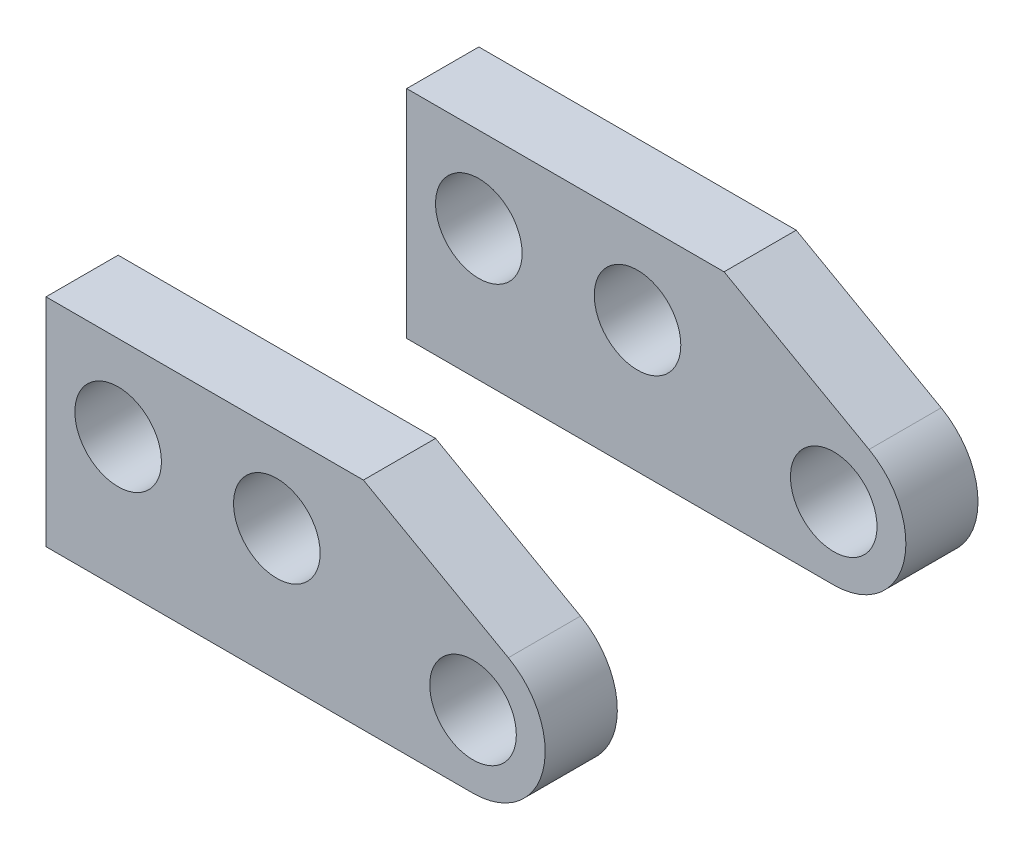
SolidWorks part; units mm, degrees
material "Thornel Mat VMA"
ref_plane "前视基准面" through (0, 0, 0) normal (0, 0, 1) x (1, 0, 0)
ref_plane "上视基准面" through (0, 0, 0) normal (0, 1, 0) x (1, 0, 0)
ref_plane "右视基准面" through (0, 0, 0) normal (1, 0, 0) x (0, 0, -1)
other "Configuration Table"
sketch "草图2" plane through (0, 0, 0) normal (0, 0, 1) x (1, 0, 0)
  line L0 (5.5, 3.75) -> (10.5237, 0.93)
  line L1 (-5.5, 3.75) -> (5.5, 3.75)
  line L2 (-5.5, 3.75) -> (-5.5, -3.75)
  line L3 (-5.5, -3.75) -> (5.5, -3.75)
  line L5 (-5.5, 3.75) -> (5.5, -3.75) construction
  line L6 (-5.5, -3.75) -> (5.5, 3.75) construction
  line L7 (5.5, -3.75) -> (9.3, -3.75)
  arc A0 (9.3, -3.75) -> (10.5237, 0.93) centre (9.3, -1.25) ccw
  circle A1 centre (9.3, -1.25) radius 1.5
  circle A2 centre (-3, 0.8) radius 1.5
  circle A3 centre (2.5, 0.8) radius 1.5
  point P0 (0, 0)
  dimension "D1" = 5
  dimension "D2" = 3
  dimension "D5" = 5.5
  dimension "D6" = 4.55
  dimension "D7" = 2.5
  dimension "D8" = 6.8
  dimension "D3" = 7.5
  dimension "D4" = 11
extrude "凸台-拉伸1" add sketch "草图2" along normal blind 2.5
sketch "草图3" plane through (0, 0, 2.5) normal (0, 0, 1) x (1, 0, 0)
  line L4 (-5.5, -3.75) -> (9.3, -3.75)
  line L5 (10.5237, 0.93) -> (5.5, 3.75)
  line L6 (5.5, 3.75) -> (-5.5, 3.75)
  line L7 (-5.5, 3.75) -> (-5.5, -3.75)
  line L8 (-5.5, -3.75) -> (9.3, -3.75)
  line L9 (10.5237, 0.93) -> (5.5, 3.75)
  line L10 (5.5, 3.75) -> (-5.5, 3.75)
  line L11 (-5.5, 3.75) -> (-5.5, -3.75)
  circle A0 centre (9.3, -1.25) radius 1.5 construction
  arc A1 (9.3, -3.75) -> (10.5237, 0.93) centre (9.3, -1.25) ccw
  arc A2 (9.3, -3.75) -> (10.5237, 0.93) centre (9.3, -1.25) ccw
  circle A3 centre (2.5, 0.8) radius 1.5 construction
  circle A4 centre (-3, 0.8) radius 1.5 construction
  circle A5 centre (9.3, -1.25) radius 1.5
  circle A6 centre (2.5, 0.8) radius 1.5
  circle A7 centre (-3, 0.8) radius 1.5
  dimension "D1" = 0
extrude "凸台-拉伸2" add sketch "草图3" along normal blind 2.5 from offset 10 separate body
